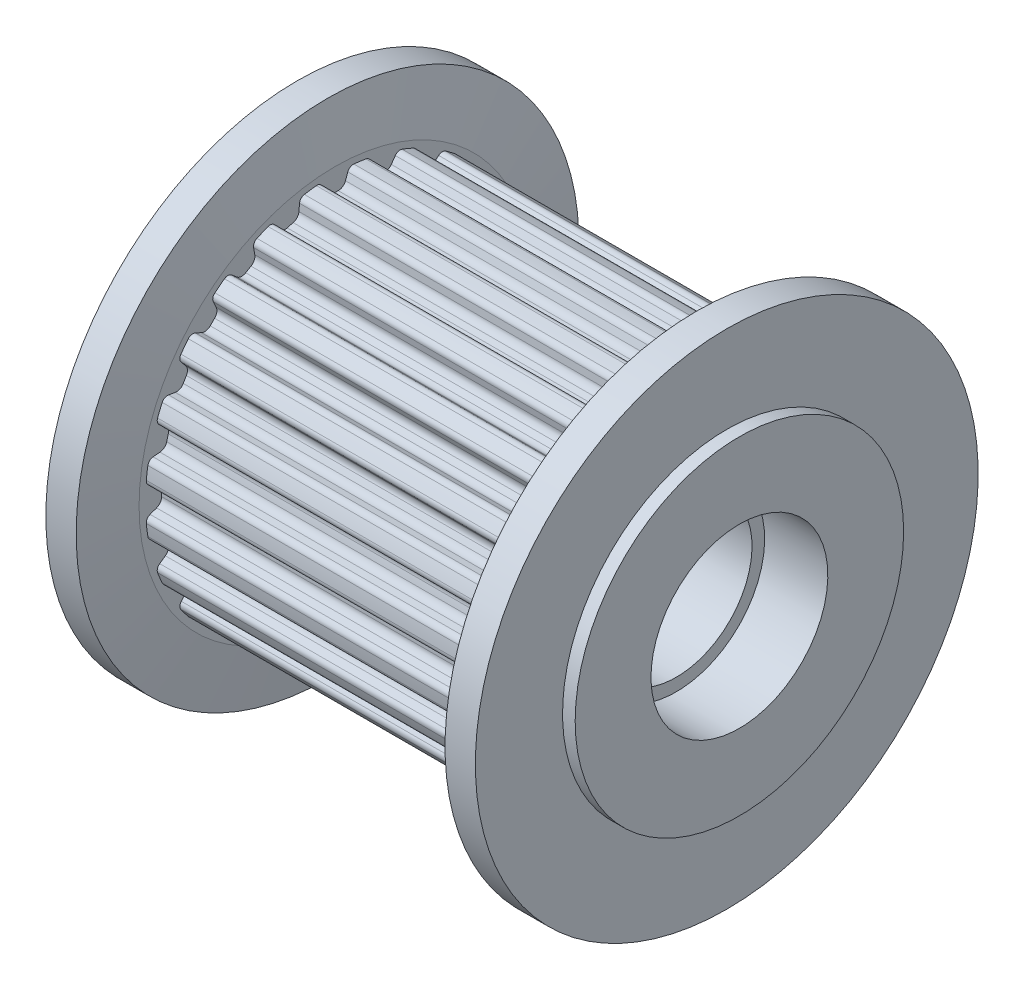
SolidWorks part; units mm, degrees
ref_plane "前视基准面" through (0, 0, 0) normal (0, 0, 1) x (1, 0, 0)
ref_plane "上视基准面" through (0, 0, 0) normal (0, 1, 0) x (1, 0, 0)
ref_plane "右视基准面" through (0, 0, 0) normal (1, 0, 0) x (0, 0, -1)
sketch "草图1" plane through (0, 0, 0) normal (0, 0, 1) x (1, 0, 0)
  line L0 (-9, 0) -> (-9, 6.5)
  line L1 (-9, 6.5) -> (-7, 6.5)
  line L2 (-7, 6.5) -> (-7, 7.51)
  line L3 (-7, 7.51) -> (7, 7.51)
  line L4 (7, 7.51) -> (7, 6.5)
  line L5 (7, 6.5) -> (9, 6.5)
  line L6 (9, 6.5) -> (9, 0)
  line L7 (9, 0) -> (-9, 0)
  dimension "D1" = 14
  dimension "D2" = 18
  dimension "D3" = 6.5
  dimension "D4" = 7.51
revolve "旋转1" add sketch "草图1" angle 360 about L7
sketch "草图3" plane through (-7, 0, 0) normal (-1, 0, 0) x (0, 0, 1)
  line L0 (-0.5632, 7.4889) -> (-0.335, 6.8618)
  line L1 (0.5632, 7.4889) -> (0.335, 6.8618)
  line L2 (0, 6.87) -> (0, 7.51) construction
  arc A0 (0.335, 6.8618) -> (-0.335, 6.8618) centre (0, 0) ccw
  arc A1 (0.5632, 7.4889) -> (-0.5632, 7.4889) centre (0, 0) ccw
  circle A2 centre (0, 0) radius 7.51 construction
  dimension "D2" = 0.64
  dimension "D1" = 20
  dimension "D3" = 0.67
extrude "切除-拉伸1" cut sketch "草图3" against normal through all
fillet "圆角1" radius 0.3 2 edges at (0, 6.8618, 0.335) (0, 6.8618, -0.335)
fillet "圆角2" radius 0.23 2 edges at (0, 7.4889, 0.5632) (0, 7.4889, -0.5632)
pattern_circular "阵列(圆周)1" count 24 over 360 about axis through (0, 0, 0) along (1, 0, 0) of "切除-拉伸1", "圆角2", "圆角1"
sketch "草图4" plane through (-7, 0, 0) normal (-1, 0, 0) x (0, 0, 1)
  line L0 (0, 6.75) -> (0, 7.51) construction
  circle A0 centre (0, 0) radius 7.76 construction
  arc A2 (0.2084, 6.7468) -> (-0.2084, 6.7468) centre (0, 0) ccw
  arc A3 (-0.65, 7.4818) -> (-0.2084, 6.7468) centre (0.65, 7.7627) ccw
  circle A4 centre (0, 0) radius 7.51 construction
  arc A5 (0.65, 7.4818) -> (0.2084, 6.7468) centre (-0.65, 7.7627) cw
  arc A6 (0.65, 7.4818) -> (-0.65, 7.4818) centre (0, 0) ccw
  dimension "D1" = 15.52
  dimension "D2" = 0.76
  dimension "D4" = 1.33
  dimension "D3" = 1.3
extrude "切除-拉伸2" [suppressed] cut sketch "草图4" against normal through all
fillet "圆角3" [suppressed] radius 0.1
fillet "圆角4" [suppressed] radius 0.19
pattern_circular "阵列(圆周)2" [suppressed] count 24 over 360
sketch "草图5" plane through (0, 0, 0) normal (0, 0, 1) x (1, 0, 0)
  line L0 (-8.5, 6.5) -> (-8.5, 9.95)
  line L2 (-8.5, 9.95) -> (-7.3, 9.95)
  line L3 (-7.3, 9.95) -> (-7, 7.76)
  line L4 (-7, 7.76) -> (-7, 6.5)
  line L5 (-7, 6.5) -> (-8.5, 6.5)
  line L6 (-9, 0) -> (9, 0) construction
  line L7 (-9, 6.5) -> (-9, -6.5) construction
  line L8 (9, -6.5) -> (9, 6.5) construction
  line L9 (0, 0) -> (0, 30.9) construction
  line L11 (-7, 7.51) -> (-7, -7.51) construction
  line L12 (8.5, 9.95) -> (7.3, 9.95)
  line L13 (7.3, 9.95) -> (7, 7.76)
  line L14 (7, 7.76) -> (7, 6.5)
  line L15 (8.5, 6.5) -> (8.5, 9.95)
  line L16 (7, 6.5) -> (8.5, 6.5)
  dimension "D1" = 9.95
  dimension "D2" = 7.76
  dimension "D3" = 0.5
  dimension "D4" = 1.2
  dimension "D5" = 6.5
revolve "旋转2" add sketch "草图5" angle 360 about L6
sketch "草图6" plane through (0, 0, 0) normal (0, 0, 1) x (1, 0, 0)
  line L0 (-9, 3.5) -> (-6.5, 3.5)
  line L1 (-9, 6.5) -> (-9, -6.5) construction
  line L2 (-6.5, 3.5) -> (-6.5, 3)
  line L3 (-6.5, 3) -> (6.5, 3)
  line L4 (6.5, 3) -> (6.5, 3.5)
  line L5 (6.5, 3.5) -> (9, 3.5)
  line L6 (9, -6.5) -> (9, 6.5) construction
  line L7 (9, 3.5) -> (9, 0)
  line L8 (9, 0) -> (-9, 0)
  line L9 (-9, 0) -> (-9, 3.5)
  dimension "D1" = 3.5
  dimension "D2" = 3
  dimension "D3" = 2.5
revolve "切除-旋转1" cut sketch "草图6" angle 360 about L8
sketch "草图7" plane through (0, 0, 0) normal (0, 0, 1) x (1, 0, 0)
  line L0 (-9, 6.5) -> (-9, -6.5) construction
  line L1 (-9, 0) -> (-6.5, 0)
  line L2 (-9, 0) -> (-9, 3.2)
  line L3 (-8.7, 3.5) -> (-6.8, 3.5)
  line L4 (-6.5, 0) -> (-6.5, 3.2)
  line L5 (9, -6.5) -> (9, 6.5) construction
  line L6 (9, 0) -> (6.5, 0)
  line L7 (9, 0) -> (9, 3.2)
  line L8 (8.7, 3.5) -> (6.8, 3.5)
  line L9 (6.5, 0) -> (6.5, 3.2)
  arc A0 (9, 3.2) -> (8.7, 3.5) centre (8.7, 3.2) ccw
  arc A1 (6.8, 3.5) -> (6.5, 3.2) centre (6.8, 3.2) ccw
  arc A2 (-6.5, 3.2) -> (-6.8, 3.5) centre (-6.8, 3.2) ccw
  arc A3 (-8.7, 3.5) -> (-9, 3.2) centre (-8.7, 3.2) ccw
  point P20 (-9, 3.5)
  dimension "D3" = 0.3
  dimension "D1" = 2.5
  dimension "D2" = 3.5
sketch "草图9" plane through (0, 0, 0) normal (0, 0, 1) x (1, 0, 0)
  line L0 (-9, 6.5) -> (-9, -6.5) construction
  line L1 (-9, 2.25) -> (-8.9, 2.25)
  line L2 (-9, 2.25) -> (-9, 1.75)
  line L3 (-9, 1.75) -> (-8.9, 1.75)
  line L4 (-8.9, 2.25) -> (-8.9, 1.75)
  line L5 (-9, 0) -> (9, 0) construction
  line L6 (9, -6.5) -> (9, 6.5) construction
  line L8 (9, 1.75) -> (8.9, 1.75)
  line L9 (9, 1.75) -> (9, 2.25)
  line L10 (9, 2.25) -> (8.9, 2.25)
  line L11 (8.9, 1.75) -> (8.9, 2.25)
  line L12 (-9, 2.45) -> (-8.9, 2.45)
  line L13 (-9, 2.45) -> (-9, 2.95)
  line L14 (-9, 2.95) -> (-8.9, 2.95)
  line L15 (-8.9, 2.45) -> (-8.9, 2.95)
  line L16 (9, 2.45) -> (8.9, 2.45)
  line L17 (9, 2.45) -> (9, 2.95)
  line L18 (9, 2.95) -> (8.9, 2.95)
  line L19 (8.9, 2.45) -> (8.9, 2.95)
  dimension "D1" = 0.1
  dimension "D2" = 0.5
  dimension "D3" = 1.75
  dimension "D4" = 2.45
sketch "Sketch1" plane through (-9, 0, 0) normal (-1, 0, 0) x (0, 0, 1)
  circle A2 centre (0, 0) radius 3.8
sketch "Sketch4" plane through (9, 0, 0) normal (1, 0, 0) x (0, 0, -1)
  circle A0 centre (0, 0) radius 3.5 construction
  circle A1 centre (0, 0) radius 3.5
  circle A2 centre (0, 0) radius 3.8
  dimension "D1" = 0.3
